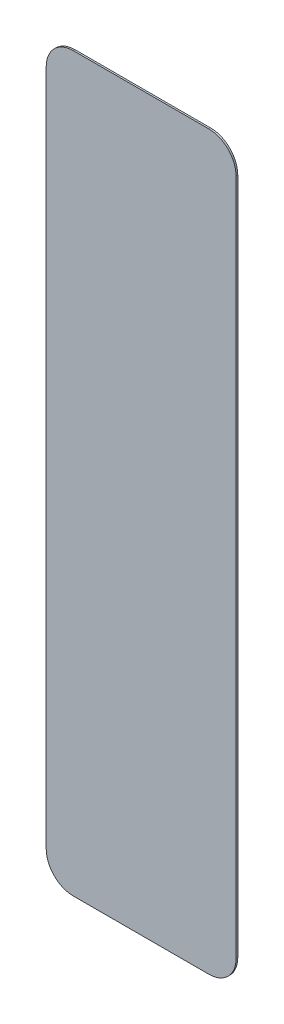
SolidWorks part; units mm, degrees
ref_plane "Front" through (0, 0, 0) normal (0, 0, 1) x (1, 0, 0)
ref_plane "Top" through (0, 0, 0) normal (0, 1, 0) x (1, 0, 0)
ref_plane "Right" through (0, 0, 0) normal (1, 0, 0) x (0, 0, -1)
sketch "Sketch1" plane through (0, 0, 0) normal (0, 0, 1) x (1, 0, 0)
  line L0 (0, -2) -> (0, -52)
  line L1 (2, -54) -> (12, -54)
  line L2 (14, -52) -> (14, -2)
  line L3 (12, 0) -> (2, 0)
  arc A0 (2, 0) -> (0, -2) centre (2, -2) ccw
  arc A1 (0, -52) -> (2, -54) centre (2, -52) ccw
  arc A2 (12, -54) -> (14, -52) centre (12, -52) ccw
  arc A3 (14, -2) -> (12, 0) centre (12, -2) ccw
  dimension "D1" = 2
  dimension "D2" = 14
  dimension "D3" = 54
extrude "Boss-Extrude1" add sketch "Sketch1" against normal blind 0.127
